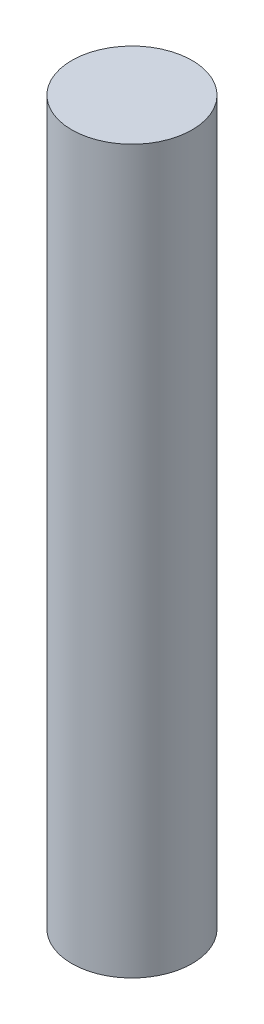
SolidWorks part; units mm, degrees
ref_plane "Front Plane" through (0, 0, 0) normal (0, 0, 1) x (1, 0, 0)
ref_plane "Top Plane" through (0, 0, 0) normal (0, 1, 0) x (1, 0, 0)
ref_plane "Right Plane" through (0, 0, 0) normal (1, 0, 0) x (0, 0, -1)
sketch "Sketch1" plane through (0, 0, 0) normal (0, 1, 0) x (1, 0, 0)
  circle A0 centre (0, 0) radius 1
  dimension "D1" = 2
extrude "Boss-Extrude1" add sketch "Sketch1" along normal blind 12
